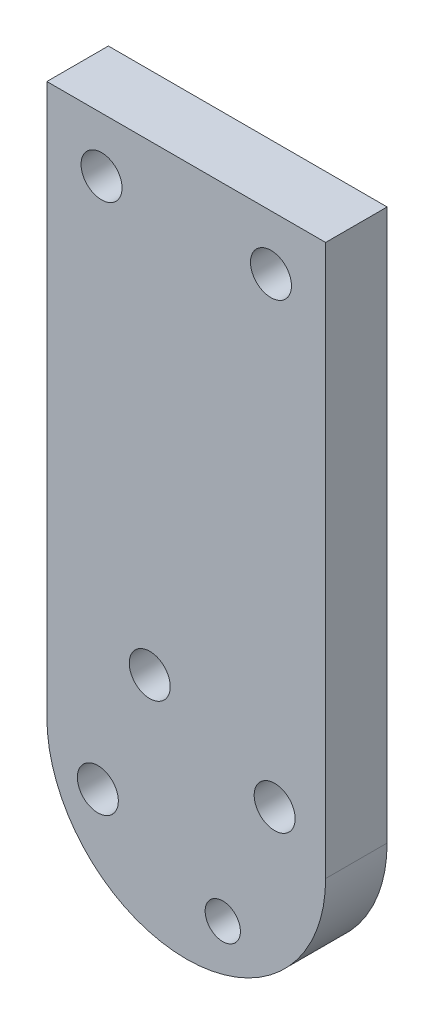
SolidWorks part; units mm, degrees
material "Acrylic (Medium-high impact)"
ref_plane "Front Plane" through (0, 0, 0) normal (0, 0, 1) x (1, 0, 0)
ref_plane "Top Plane" through (0, 0, 0) normal (0, 1, 0) x (1, 0, 0)
ref_plane "Right Plane" through (0, 0, 0) normal (1, 0, 0) x (0, 0, -1)
sketch "Sketch1" plane through (0, 0, 0) normal (0, 0, 1) x (1, 0, 0)
  line L1 (0, 0) -> (-20.4, 0)
  line L2 (0, 0) -> (0, 40.3153)
  line L3 (0, 40.3153) -> (-20.4, 40.3153)
  line L4 (-20.4, 0) -> (-20.4, 40.3153)
  circle A0 centre (-10.2, 0) radius 10.2
  circle A1 centre (-3.7298, 2.6714) radius 1.5
  circle A2 centre (-7.5286, -6.4702) radius 1.2899
  circle A3 centre (-16.6702, -2.6714) radius 1.5
  circle A4 centre (-12.8714, 6.4702) radius 1.5
  circle A5 centre (-16.4, 36.3153) radius 1.5
  circle A6 centre (-4, 36.3153) radius 1.5
  dimension "D2" = 3
  dimension "D3" = 3
  dimension "D4" = 4
  dimension "D5" = 4
  dimension "D6" = 4
  dimension "D7" = 4
extrude "Boss-Extrude1" add sketch "Sketch1" along normal blind 4.5 contours A0 L2 L3 L4 A6 A5 | L1 A0 A3 A2 | L1 A0 A4 A1
